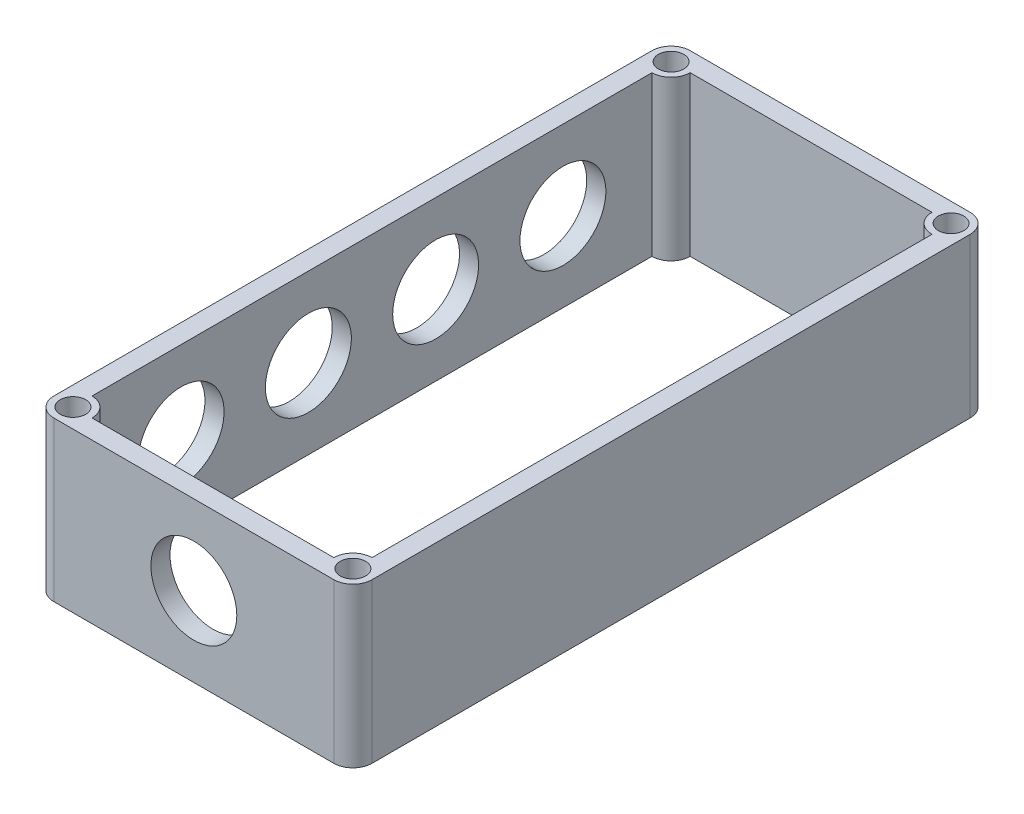
SolidWorks part; units mm, degrees
ref_plane "Front Plane" through (0, 0, 0) normal (0, 0, 1) x (1, 0, 0)
ref_plane "Top Plane" through (0, 0, 0) normal (0, 1, 0) x (1, 0, 0)
ref_plane "Right Plane" through (0, 0, 0) normal (1, 0, 0) x (0, 0, -1)
sketch "Sketch1" plane through (0, 0, 0) normal (0, 1, 0) x (1, 0, 0)
  line L1 (-22, -50) -> (22, -50)
  line L2 (-25, -47) -> (-25, 47)
  line L3 (-22, 50) -> (22, 50)
  line L4 (25, -47) -> (25, 47)
  line L5 (-25, -50) -> (25, 50) construction
  line L6 (-25, 50) -> (25, -50) construction
  line L7 (-22, -47) -> (22, -47)
  line L8 (-22, -47) -> (-22, 47)
  line L9 (-22, 47) -> (22, 47)
  line L10 (22, -47) -> (22, 47)
  line L11 (-22, -47) -> (22, 47) construction
  line L12 (-22, 47) -> (22, -47) construction
  arc A0 (-22, -50) -> (-25, -47) centre (-22, -47) cw
  arc A1 (22, -50) -> (25, -47) centre (22, -47) ccw
  arc A2 (22, 50) -> (25, 47) centre (22, 47) cw
  arc A3 (-25, 47) -> (-22, 50) centre (-22, 47) cw
  circle A4 centre (-22, 47) radius 2
  circle A5 centre (22, 47) radius 2
  circle A6 centre (22, -47) radius 2
  circle A7 centre (-22, -47) radius 2
  circle A8 centre (-22, 47) radius 3
  circle A9 centre (22, 47) radius 3
  circle A10 centre (22, -47) radius 3
  circle A11 centre (-22, -47) radius 3
  point P0 (0, 0)
  point P26 (0, 0)
  dimension "D3" = 3
  dimension "D4" = 4
  dimension "D1" = 100
  dimension "D2" = 50
extrude "Boss-Extrude1" add sketch "Sketch1" along normal blind 25 contours A9 L3 A8 L9 | L9 A8 A3 L8 A4 | L8 A8 L9 A4 | A11 L8 A8 L2 | L10 A9 A2 L9 A5 | L9 A9 L10 A5 | A10 L4 A9 L10 | A11 L1 A10 L7 | L7 A11 L8 A7 | A0 A11 L7 A7 L8 | A1 A10 L10 A6 L7 | L10 A10 L7 A6
sketch "Sketch2" plane through (0, 0, 50) normal (0, 0, 1) x (1, 0, 0)
  line L1 (-22, 25) -> (-22, 0) construction
  circle A0 centre (0, 12.5) radius 6.75
  point P2 (0, 0)
  point P4 (-29.7817, 8.1757)
  point P5 (-22, 12.5)
  point P6 (-22, 12.5)
  point P9 (0, 0)
  point P10 (0, 12.5)
  dimension "D1" = 13.5
extrude "Cut-Extrude1" cut sketch "Sketch2" against normal up to next
sketch "Sketch3" plane through (-25, 0, 0) normal (-1, 0, 0) x (0, 0, 1)
  line L0 (0, 0) -> (0, 25) construction
  line L1 (47, 25) -> (-47, 25) construction
  circle A0 centre (-30, 12.5) radius 6.75
  circle A3 centre (-10, 12.5) radius 6.75
  circle A4 centre (10, 12.5) radius 6.75
  circle A5 centre (30, 12.5) radius 6.75
  point P5 (0, 12.5)
  point P14 (0, 0)
  dimension "D2" = 13.5
  dimension "D1" = 20
  dimension "D3" = 20
extrude "Cut-Extrude2" cut sketch "Sketch3" against normal up to next
